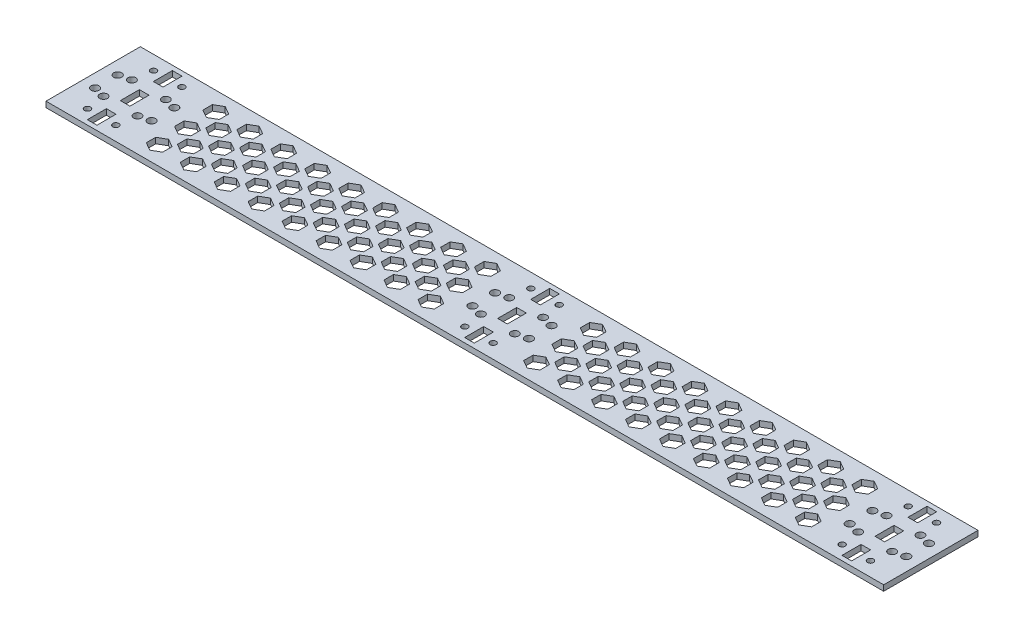
SolidWorks part; units mm, degrees
ref_plane "前视基准面" through (0, 0, 0) normal (0, 0, 1) x (1, 0, 0)
ref_plane "上视基准面" through (0, 0, 0) normal (0, 1, 0) x (1, 0, 0)
ref_plane "右视基准面" through (0, 0, 0) normal (1, 0, 0) x (0, 0, -1)
other "Configuration Table"
sketch "草图1" plane through (0, 0, 0) normal (0, 1, 0) x (1, 0, 0)
  line L0 (202.55, -5.05) -> (197.45, -5.05)
  line L1 (222, -25) -> (-222, -25)
  line L2 (222, -25) -> (222, 25)
  line L3 (222, 25) -> (-222, 25)
  line L4 (-222, -25) -> (-222, 25)
  line L5 (222, -25) -> (-222, 25) construction
  line L6 (222, 25) -> (-222, -25) construction
  line L7 (19, -10) -> (-19, -10) construction
  line L8 (19, -10) -> (19, 10) construction
  line L9 (19, 10) -> (-19, 10) construction
  line L10 (-19, -10) -> (-19, 10) construction
  line L11 (19, -10) -> (-19, 10) construction
  line L12 (19, 10) -> (-19, -10) construction
  line L13 (2.55, -5.05) -> (-2.55, -5.05)
  line L14 (2.55, -5.05) -> (2.55, 5.05)
  line L15 (2.55, 5.05) -> (-2.55, 5.05)
  line L16 (-2.55, -5.05) -> (-2.55, 5.05)
  line L17 (2.55, -5.05) -> (-2.55, 5.05) construction
  line L18 (2.55, 5.05) -> (-2.55, -5.05) construction
  line L19 (2.55, 12.45) -> (-2.55, 12.45)
  line L20 (2.55, 12.45) -> (2.55, 22.55)
  line L21 (2.55, 22.55) -> (-2.55, 22.55)
  line L22 (-2.55, 12.45) -> (-2.55, 22.55)
  line L23 (2.55, 12.45) -> (-2.55, 22.55) construction
  line L24 (2.55, 22.55) -> (-2.55, 12.45) construction
  line L25 (2.55, -22.55) -> (-2.55, -22.55)
  line L26 (2.55, -22.55) -> (2.55, -12.45)
  line L27 (2.55, -12.45) -> (-2.55, -12.45)
  line L28 (-2.55, -22.55) -> (-2.55, -12.45)
  line L29 (2.55, -22.55) -> (-2.55, -12.45) construction
  line L30 (2.55, -12.45) -> (-2.55, -22.55) construction
  line L31 (202.55, -5.05) -> (202.55, 5.05)
  line L32 (202.55, 5.05) -> (197.45, 5.05)
  line L33 (197.45, -5.05) -> (197.45, 5.05)
  line L34 (202.55, 12.45) -> (197.45, 12.45)
  line L35 (202.55, 12.45) -> (202.55, 22.55)
  line L36 (202.55, 22.55) -> (197.45, 22.55)
  line L37 (197.45, 12.45) -> (197.45, 22.55)
  line L38 (202.55, -22.55) -> (197.45, -22.55)
  line L39 (202.55, -22.55) -> (202.55, -12.45)
  line L40 (202.55, -12.45) -> (197.45, -12.45)
  line L41 (197.45, -22.55) -> (197.45, -12.45)
  line L42 (219, -10) -> (181, -10) construction
  line L43 (219, -10) -> (219, 10) construction
  line L44 (219, 10) -> (181, 10) construction
  line L45 (181, -10) -> (181, 10) construction
  line L46 (219, -10) -> (181, 10) construction
  line L47 (219, 10) -> (181, -10) construction
  line L48 (202.55, -5.05) -> (197.45, 5.05) construction
  line L49 (202.55, 5.05) -> (197.45, -5.05) construction
  line L50 (202.55, 12.45) -> (197.45, 22.55) construction
  line L51 (202.55, 22.55) -> (197.45, 12.45) construction
  line L52 (202.55, -22.55) -> (197.45, -12.45) construction
  line L53 (202.55, -12.45) -> (197.45, -22.55) construction
  line L54 (-197.45, -5.05) -> (-202.55, -5.05)
  line L55 (-197.45, -5.05) -> (-197.45, 5.05)
  line L56 (-197.45, 5.05) -> (-202.55, 5.05)
  line L57 (-202.55, -5.05) -> (-202.55, 5.05)
  line L58 (-197.45, 12.45) -> (-202.55, 12.45)
  line L59 (-197.45, 12.45) -> (-197.45, 22.55)
  line L60 (-197.45, 22.55) -> (-202.55, 22.55)
  line L61 (-202.55, 12.45) -> (-202.55, 22.55)
  line L62 (-197.45, -22.55) -> (-202.55, -22.55)
  line L63 (-197.45, -22.55) -> (-197.45, -12.45)
  line L64 (-197.45, -12.45) -> (-202.55, -12.45)
  line L65 (-202.55, -22.55) -> (-202.55, -12.45)
  line L66 (-181, -10) -> (-219, -10) construction
  line L67 (-181, -10) -> (-181, 10) construction
  line L68 (-181, 10) -> (-219, 10) construction
  line L69 (-219, -10) -> (-219, 10) construction
  line L70 (-181, -10) -> (-219, 10) construction
  line L71 (-181, 10) -> (-219, -10) construction
  line L72 (-197.45, -5.05) -> (-202.55, 5.05) construction
  line L73 (-197.45, 5.05) -> (-202.55, -5.05) construction
  line L74 (-197.45, 12.45) -> (-202.55, 22.55) construction
  line L75 (-197.45, 22.55) -> (-202.55, 12.45) construction
  line L76 (-197.45, -22.55) -> (-202.55, -12.45) construction
  line L77 (-197.45, -12.45) -> (-202.55, -22.55) construction
  line L78 (-55, 12.5) -> (-59.3301, 10)
  line L79 (-28, 5) -> (-32.3301, 2.5)
  line L80 (-32.3301, 2.5) -> (-32.3301, -2.5)
  line L81 (-32.3301, -2.5) -> (-28, -5)
  line L82 (-28, -5) -> (-23.6699, -2.5)
  line L83 (-23.6699, -2.5) -> (-23.6699, 2.5)
  line L84 (-23.6699, 2.5) -> (-28, 5)
  line L85 (-28, 20) -> (-32.3301, 17.5)
  line L86 (-32.3301, 17.5) -> (-32.3301, 12.5)
  line L87 (-32.3301, 12.5) -> (-28, 10)
  line L88 (-28, 10) -> (-23.6699, 12.5)
  line L89 (-23.6699, 12.5) -> (-23.6699, 17.5)
  line L90 (-23.6699, 17.5) -> (-28, 20)
  line L91 (-28, -20) -> (-23.6699, -17.5)
  line L92 (-23.6699, -17.5) -> (-23.6699, -12.5)
  line L93 (-23.6699, -12.5) -> (-28, -10)
  line L94 (-28, -10) -> (-32.3301, -12.5)
  line L95 (-32.3301, -12.5) -> (-32.3301, -17.5)
  line L96 (-32.3301, -17.5) -> (-28, -20)
  line L97 (-37, 12.5) -> (-41.3301, 10)
  line L98 (-41.3301, 10) -> (-41.3301, 5)
  line L99 (-41.3301, 5) -> (-37, 2.5)
  line L100 (-37, 2.5) -> (-32.6699, 5)
  line L101 (-32.6699, 5) -> (-32.6699, 10)
  line L102 (-32.6699, 10) -> (-37, 12.5)
  line L103 (-37, -12.5) -> (-32.6699, -10)
  line L104 (-32.6699, -10) -> (-32.6699, -5)
  line L105 (-32.6699, -5) -> (-37, -2.5)
  line L106 (-37, -2.5) -> (-41.3301, -5)
  line L107 (-41.3301, -5) -> (-41.3301, -10)
  line L108 (-41.3301, -10) -> (-37, -12.5)
  line L109 (-59.3301, 10) -> (-59.3301, 5)
  line L110 (-59.3301, 5) -> (-55, 2.5)
  line L111 (-55, 2.5) -> (-50.6699, 5)
  line L112 (-50.6699, 5) -> (-50.6699, 10)
  line L113 (-50.6699, 10) -> (-55, 12.5)
  line L114 (-46, 20) -> (-50.3301, 17.5)
  line L115 (-50.3301, 17.5) -> (-50.3301, 12.5)
  line L116 (-50.3301, 12.5) -> (-46, 10)
  line L117 (-46, 10) -> (-41.6699, 12.5)
  line L118 (-41.6699, 12.5) -> (-41.6699, 17.5)
  line L119 (-41.6699, 17.5) -> (-46, 20)
  line L120 (-46, -20) -> (-41.6699, -17.5)
  line L121 (-41.6699, -17.5) -> (-41.6699, -12.5)
  line L122 (-41.6699, -12.5) -> (-46, -10)
  line L123 (-46, -10) -> (-50.3301, -12.5)
  line L124 (-50.3301, -12.5) -> (-50.3301, -17.5)
  line L125 (-50.3301, -17.5) -> (-46, -20)
  line L126 (-55, -12.5) -> (-50.6699, -10)
  line L127 (-50.6699, -10) -> (-50.6699, -5)
  line L128 (-50.6699, -5) -> (-55, -2.5)
  line L129 (-55, -2.5) -> (-59.3301, -5)
  line L130 (-59.3301, -5) -> (-59.3301, -10)
  line L131 (-59.3301, -10) -> (-55, -12.5)
  line L132 (-46, 5) -> (-50.3301, 2.5)
  line L133 (-50.3301, 2.5) -> (-50.3301, -2.5)
  line L134 (-50.3301, -2.5) -> (-46, -5)
  line L135 (-46, -5) -> (-41.6699, -2.5)
  line L136 (-41.6699, -2.5) -> (-41.6699, 2.5)
  line L137 (-41.6699, 2.5) -> (-46, 5)
  line L138 (-73, 12.5) -> (-77.3301, 10)
  line L139 (-77.3301, 10) -> (-77.3301, 5)
  line L140 (-77.3301, 5) -> (-73, 2.5)
  line L141 (-73, 2.5) -> (-68.6699, 5)
  line L142 (-68.6699, 5) -> (-68.6699, 10)
  line L143 (-68.6699, 10) -> (-73, 12.5)
  line L144 (-64, 20) -> (-68.3301, 17.5)
  line L145 (-68.3301, 17.5) -> (-68.3301, 12.5)
  line L146 (-68.3301, 12.5) -> (-64, 10)
  line L147 (-64, 10) -> (-59.6699, 12.5)
  line L148 (-59.6699, 12.5) -> (-59.6699, 17.5)
  line L149 (-59.6699, 17.5) -> (-64, 20)
  line L150 (-64, -20) -> (-59.6699, -17.5)
  line L151 (-59.6699, -17.5) -> (-59.6699, -12.5)
  line L152 (-59.6699, -12.5) -> (-64, -10)
  line L153 (-64, -10) -> (-68.3301, -12.5)
  line L154 (-68.3301, -12.5) -> (-68.3301, -17.5)
  line L155 (-68.3301, -17.5) -> (-64, -20)
  line L156 (-73, -12.5) -> (-68.6699, -10)
  line L157 (-68.6699, -10) -> (-68.6699, -5)
  line L158 (-68.6699, -5) -> (-73, -2.5)
  line L159 (-73, -2.5) -> (-77.3301, -5)
  line L160 (-77.3301, -5) -> (-77.3301, -10)
  line L161 (-77.3301, -10) -> (-73, -12.5)
  line L162 (-64, 5) -> (-68.3301, 2.5)
  line L163 (-68.3301, 2.5) -> (-68.3301, -2.5)
  line L164 (-68.3301, -2.5) -> (-64, -5)
  line L165 (-64, -5) -> (-59.6699, -2.5)
  line L166 (-59.6699, -2.5) -> (-59.6699, 2.5)
  line L167 (-59.6699, 2.5) -> (-64, 5)
  line L168 (-91, 12.5) -> (-95.3301, 10)
  line L169 (-95.3301, 10) -> (-95.3301, 5)
  line L170 (-95.3301, 5) -> (-91, 2.5)
  line L171 (-91, 2.5) -> (-86.6699, 5)
  line L172 (-86.6699, 5) -> (-86.6699, 10)
  line L173 (-86.6699, 10) -> (-91, 12.5)
  line L174 (-82, 20) -> (-86.3301, 17.5)
  line L175 (-86.3301, 17.5) -> (-86.3301, 12.5)
  line L176 (-86.3301, 12.5) -> (-82, 10)
  line L177 (-82, 10) -> (-77.6699, 12.5)
  line L178 (-77.6699, 12.5) -> (-77.6699, 17.5)
  line L179 (-77.6699, 17.5) -> (-82, 20)
  line L180 (-82, -20) -> (-77.6699, -17.5)
  line L181 (-77.6699, -17.5) -> (-77.6699, -12.5)
  line L182 (-77.6699, -12.5) -> (-82, -10)
  line L183 (-82, -10) -> (-86.3301, -12.5)
  line L184 (-86.3301, -12.5) -> (-86.3301, -17.5)
  line L185 (-86.3301, -17.5) -> (-82, -20)
  line L186 (-91, -12.5) -> (-86.6699, -10)
  line L187 (-86.6699, -10) -> (-86.6699, -5)
  line L188 (-86.6699, -5) -> (-91, -2.5)
  line L189 (-91, -2.5) -> (-95.3301, -5)
  line L190 (-95.3301, -5) -> (-95.3301, -10)
  line L191 (-95.3301, -10) -> (-91, -12.5)
  line L192 (-82, 5) -> (-86.3301, 2.5)
  line L193 (-86.3301, 2.5) -> (-86.3301, -2.5)
  line L194 (-86.3301, -2.5) -> (-82, -5)
  line L195 (-82, -5) -> (-77.6699, -2.5)
  line L196 (-77.6699, -2.5) -> (-77.6699, 2.5)
  line L197 (-77.6699, 2.5) -> (-82, 5)
  line L198 (-109, 12.5) -> (-113.3301, 10)
  line L199 (-113.3301, 10) -> (-113.3301, 5)
  line L200 (-113.3301, 5) -> (-109, 2.5)
  line L201 (-109, 2.5) -> (-104.6699, 5)
  line L202 (-104.6699, 5) -> (-104.6699, 10)
  line L203 (-104.6699, 10) -> (-109, 12.5)
  line L204 (-100, 20) -> (-104.3301, 17.5)
  line L205 (-104.3301, 17.5) -> (-104.3301, 12.5)
  line L206 (-104.3301, 12.5) -> (-100, 10)
  line L207 (-100, 10) -> (-95.6699, 12.5)
  line L208 (-95.6699, 12.5) -> (-95.6699, 17.5)
  line L209 (-95.6699, 17.5) -> (-100, 20)
  line L210 (-100, -20) -> (-95.6699, -17.5)
  line L211 (-95.6699, -17.5) -> (-95.6699, -12.5)
  line L212 (-95.6699, -12.5) -> (-100, -10)
  line L213 (-100, -10) -> (-104.3301, -12.5)
  line L214 (-104.3301, -12.5) -> (-104.3301, -17.5)
  line L215 (-104.3301, -17.5) -> (-100, -20)
  line L216 (-109, -12.5) -> (-104.6699, -10)
  line L217 (-104.6699, -10) -> (-104.6699, -5)
  line L218 (-104.6699, -5) -> (-109, -2.5)
  line L219 (-109, -2.5) -> (-113.3301, -5)
  line L220 (-113.3301, -5) -> (-113.3301, -10)
  line L221 (-113.3301, -10) -> (-109, -12.5)
  line L222 (-100, 5) -> (-104.3301, 2.5)
  line L223 (-104.3301, 2.5) -> (-104.3301, -2.5)
  line L224 (-104.3301, -2.5) -> (-100, -5)
  line L225 (-100, -5) -> (-95.6699, -2.5)
  line L226 (-95.6699, -2.5) -> (-95.6699, 2.5)
  line L227 (-95.6699, 2.5) -> (-100, 5)
  line L228 (-127, 12.5) -> (-131.3301, 10)
  line L229 (-131.3301, 10) -> (-131.3301, 5)
  line L230 (-131.3301, 5) -> (-127, 2.5)
  line L231 (-127, 2.5) -> (-122.6699, 5)
  line L232 (-122.6699, 5) -> (-122.6699, 10)
  line L233 (-122.6699, 10) -> (-127, 12.5)
  line L234 (-118, 20) -> (-122.3301, 17.5)
  line L235 (-122.3301, 17.5) -> (-122.3301, 12.5)
  line L236 (-122.3301, 12.5) -> (-118, 10)
  line L237 (-118, 10) -> (-113.6699, 12.5)
  line L238 (-113.6699, 12.5) -> (-113.6699, 17.5)
  line L239 (-113.6699, 17.5) -> (-118, 20)
  line L240 (-118, -20) -> (-113.6699, -17.5)
  line L241 (-113.6699, -17.5) -> (-113.6699, -12.5)
  line L242 (-113.6699, -12.5) -> (-118, -10)
  line L243 (-118, -10) -> (-122.3301, -12.5)
  line L244 (-122.3301, -12.5) -> (-122.3301, -17.5)
  line L245 (-122.3301, -17.5) -> (-118, -20)
  line L246 (-127, -12.5) -> (-122.6699, -10)
  line L247 (-122.6699, -10) -> (-122.6699, -5)
  line L248 (-122.6699, -5) -> (-127, -2.5)
  line L249 (-127, -2.5) -> (-131.3301, -5)
  line L250 (-131.3301, -5) -> (-131.3301, -10)
  line L251 (-131.3301, -10) -> (-127, -12.5)
  line L252 (-118, 5) -> (-122.3301, 2.5)
  line L253 (-122.3301, 2.5) -> (-122.3301, -2.5)
  line L254 (-122.3301, -2.5) -> (-118, -5)
  line L255 (-118, -5) -> (-113.6699, -2.5)
  line L256 (-113.6699, -2.5) -> (-113.6699, 2.5)
  line L257 (-113.6699, 2.5) -> (-118, 5)
  line L258 (-145, 12.5) -> (-149.3301, 10)
  line L259 (-149.3301, 10) -> (-149.3301, 5)
  line L260 (-149.3301, 5) -> (-145, 2.5)
  line L261 (-145, 2.5) -> (-140.6699, 5)
  line L262 (-140.6699, 5) -> (-140.6699, 10)
  line L263 (-140.6699, 10) -> (-145, 12.5)
  line L264 (-136, 20) -> (-140.3301, 17.5)
  line L265 (-140.3301, 17.5) -> (-140.3301, 12.5)
  line L266 (-140.3301, 12.5) -> (-136, 10)
  line L267 (-136, 10) -> (-131.6699, 12.5)
  line L268 (-131.6699, 12.5) -> (-131.6699, 17.5)
  line L269 (-131.6699, 17.5) -> (-136, 20)
  line L270 (-136, -20) -> (-131.6699, -17.5)
  line L271 (-131.6699, -17.5) -> (-131.6699, -12.5)
  line L272 (-131.6699, -12.5) -> (-136, -10)
  line L273 (-136, -10) -> (-140.3301, -12.5)
  line L274 (-140.3301, -12.5) -> (-140.3301, -17.5)
  line L275 (-140.3301, -17.5) -> (-136, -20)
  line L276 (-145, -12.5) -> (-140.6699, -10)
  line L277 (-140.6699, -10) -> (-140.6699, -5)
  line L278 (-140.6699, -5) -> (-145, -2.5)
  line L279 (-145, -2.5) -> (-149.3301, -5)
  line L280 (-149.3301, -5) -> (-149.3301, -10)
  line L281 (-149.3301, -10) -> (-145, -12.5)
  line L282 (-136, 5) -> (-140.3301, 2.5)
  line L283 (-140.3301, 2.5) -> (-140.3301, -2.5)
  line L284 (-140.3301, -2.5) -> (-136, -5)
  line L285 (-136, -5) -> (-131.6699, -2.5)
  line L286 (-131.6699, -2.5) -> (-131.6699, 2.5)
  line L287 (-131.6699, 2.5) -> (-136, 5)
  line L288 (-163, 12.5) -> (-167.3301, 10)
  line L289 (-167.3301, 10) -> (-167.3301, 5)
  line L290 (-167.3301, 5) -> (-163, 2.5)
  line L291 (-163, 2.5) -> (-158.6699, 5)
  line L292 (-158.6699, 5) -> (-158.6699, 10)
  line L293 (-158.6699, 10) -> (-163, 12.5)
  line L294 (-154, 20) -> (-158.3301, 17.5)
  line L295 (-158.3301, 17.5) -> (-158.3301, 12.5)
  line L296 (-158.3301, 12.5) -> (-154, 10)
  line L297 (-154, 10) -> (-149.6699, 12.5)
  line L298 (-149.6699, 12.5) -> (-149.6699, 17.5)
  line L299 (-149.6699, 17.5) -> (-154, 20)
  line L300 (-154, -20) -> (-149.6699, -17.5)
  line L301 (-149.6699, -17.5) -> (-149.6699, -12.5)
  line L302 (-149.6699, -12.5) -> (-154, -10)
  line L303 (-154, -10) -> (-158.3301, -12.5)
  line L304 (-158.3301, -12.5) -> (-158.3301, -17.5)
  line L305 (-158.3301, -17.5) -> (-154, -20)
  line L306 (-163, -12.5) -> (-158.6699, -10)
  line L307 (-158.6699, -10) -> (-158.6699, -5)
  line L308 (-158.6699, -5) -> (-163, -2.5)
  line L309 (-163, -2.5) -> (-167.3301, -5)
  line L310 (-167.3301, -5) -> (-167.3301, -10)
  line L311 (-167.3301, -10) -> (-163, -12.5)
  line L312 (-154, 5) -> (-158.3301, 2.5)
  line L313 (-158.3301, 2.5) -> (-158.3301, -2.5)
  line L314 (-158.3301, -2.5) -> (-154, -5)
  line L315 (-154, -5) -> (-149.6699, -2.5)
  line L316 (-149.6699, -2.5) -> (-149.6699, 2.5)
  line L317 (-149.6699, 2.5) -> (-154, 5)
  line L318 (-172, 20) -> (-176.3301, 17.5)
  line L319 (-176.3301, 17.5) -> (-176.3301, 12.5)
  line L320 (-176.3301, 12.5) -> (-172, 10)
  line L321 (-172, 10) -> (-167.6699, 12.5)
  line L322 (-167.6699, 12.5) -> (-167.6699, 17.5)
  line L323 (-167.6699, 17.5) -> (-172, 20)
  line L324 (-172, 5) -> (-176.3301, 2.5)
  line L325 (-176.3301, 2.5) -> (-176.3301, -2.5)
  line L326 (-176.3301, -2.5) -> (-172, -5)
  line L327 (-172, -5) -> (-167.6699, -2.5)
  line L328 (-167.6699, -2.5) -> (-167.6699, 2.5)
  line L329 (-167.6699, 2.5) -> (-172, 5)
  line L330 (-172, -20) -> (-167.6699, -17.5)
  line L331 (-167.6699, -17.5) -> (-167.6699, -12.5)
  line L332 (-167.6699, -12.5) -> (-172, -10)
  line L333 (-172, -10) -> (-176.3301, -12.5)
  line L334 (-176.3301, -12.5) -> (-176.3301, -17.5)
  line L335 (-176.3301, -17.5) -> (-172, -20)
  line L336 (0, 45.3453) -> (0, -42.6317) construction
  line L337 (23.6699, 17.5) -> (28, 20)
  line L338 (23.6699, 12.5) -> (23.6699, 17.5)
  line L339 (28, 10) -> (23.6699, 12.5)
  line L340 (32.3301, 12.5) -> (28, 10)
  line L341 (32.3301, 17.5) -> (32.3301, 12.5)
  line L342 (28, 20) -> (32.3301, 17.5)
  line L343 (23.6699, 2.5) -> (28, 5)
  line L344 (23.6699, -2.5) -> (23.6699, 2.5)
  line L345 (28, -5) -> (23.6699, -2.5)
  line L346 (32.3301, -2.5) -> (28, -5)
  line L347 (32.3301, 2.5) -> (32.3301, -2.5)
  line L348 (28, 5) -> (32.3301, 2.5)
  line L349 (32.3301, -17.5) -> (28, -20)
  line L350 (32.3301, -12.5) -> (32.3301, -17.5)
  line L351 (28, -10) -> (32.3301, -12.5)
  line L352 (23.6699, -12.5) -> (28, -10)
  line L353 (23.6699, -17.5) -> (23.6699, -12.5)
  line L354 (28, -20) -> (23.6699, -17.5)
  line L355 (32.6699, 10) -> (37, 12.5)
  line L356 (32.6699, 5) -> (32.6699, 10)
  line L357 (37, 2.5) -> (32.6699, 5)
  line L358 (41.3301, 5) -> (37, 2.5)
  line L359 (41.3301, 10) -> (41.3301, 5)
  line L360 (37, 12.5) -> (41.3301, 10)
  line L361 (41.3301, -10) -> (37, -12.5)
  line L362 (41.3301, -5) -> (41.3301, -10)
  line L363 (37, -2.5) -> (41.3301, -5)
  line L364 (32.6699, -5) -> (37, -2.5)
  line L365 (32.6699, -10) -> (32.6699, -5)
  line L366 (37, -12.5) -> (32.6699, -10)
  line L367 (50.3301, -17.5) -> (46, -20)
  line L368 (50.3301, -12.5) -> (50.3301, -17.5)
  line L369 (46, -10) -> (50.3301, -12.5)
  line L370 (41.6699, -12.5) -> (46, -10)
  line L371 (41.6699, -17.5) -> (41.6699, -12.5)
  line L372 (46, -20) -> (41.6699, -17.5)
  line L373 (41.6699, 2.5) -> (46, 5)
  line L374 (41.6699, -2.5) -> (41.6699, 2.5)
  line L375 (46, -5) -> (41.6699, -2.5)
  line L376 (50.3301, -2.5) -> (46, -5)
  line L377 (50.3301, 2.5) -> (50.3301, -2.5)
  line L378 (46, 5) -> (50.3301, 2.5)
  line L379 (41.6699, 17.5) -> (46, 20)
  line L380 (41.6699, 12.5) -> (41.6699, 17.5)
  line L381 (46, 10) -> (41.6699, 12.5)
  line L382 (50.3301, 12.5) -> (46, 10)
  line L383 (50.3301, 17.5) -> (50.3301, 12.5)
  line L384 (46, 20) -> (50.3301, 17.5)
  line L385 (50.6699, 10) -> (55, 12.5)
  line L386 (50.6699, 5) -> (50.6699, 10)
  line L387 (55, 2.5) -> (50.6699, 5)
  line L388 (59.3301, 5) -> (55, 2.5)
  line L389 (59.3301, 10) -> (59.3301, 5)
  line L390 (55, 12.5) -> (59.3301, 10)
  line L391 (59.3301, -10) -> (55, -12.5)
  line L392 (59.3301, -5) -> (59.3301, -10)
  line L393 (55, -2.5) -> (59.3301, -5)
  line L394 (50.6699, -5) -> (55, -2.5)
  line L395 (50.6699, -10) -> (50.6699, -5)
  line L396 (55, -12.5) -> (50.6699, -10)
  line L397 (68.3301, -17.5) -> (64, -20)
  line L398 (68.3301, -12.5) -> (68.3301, -17.5)
  line L399 (64, -10) -> (68.3301, -12.5)
  line L400 (59.6699, -12.5) -> (64, -10)
  line L401 (59.6699, -17.5) -> (59.6699, -12.5)
  line L402 (64, -20) -> (59.6699, -17.5)
  line L403 (59.6699, 2.5) -> (64, 5)
  line L404 (59.6699, -2.5) -> (59.6699, 2.5)
  line L405 (64, -5) -> (59.6699, -2.5)
  line L406 (68.3301, -2.5) -> (64, -5)
  line L407 (68.3301, 2.5) -> (68.3301, -2.5)
  line L408 (64, 5) -> (68.3301, 2.5)
  line L409 (59.6699, 17.5) -> (64, 20)
  line L410 (59.6699, 12.5) -> (59.6699, 17.5)
  line L411 (64, 10) -> (59.6699, 12.5)
  line L412 (68.3301, 12.5) -> (64, 10)
  line L413 (68.3301, 17.5) -> (68.3301, 12.5)
  line L414 (64, 20) -> (68.3301, 17.5)
  line L415 (68.6699, 10) -> (73, 12.5)
  line L416 (68.6699, 5) -> (68.6699, 10)
  line L417 (73, 2.5) -> (68.6699, 5)
  line L418 (77.3301, 5) -> (73, 2.5)
  line L419 (77.3301, 10) -> (77.3301, 5)
  line L420 (73, 12.5) -> (77.3301, 10)
  line L421 (77.3301, -10) -> (73, -12.5)
  line L422 (77.3301, -5) -> (77.3301, -10)
  line L423 (73, -2.5) -> (77.3301, -5)
  line L424 (68.6699, -5) -> (73, -2.5)
  line L425 (68.6699, -10) -> (68.6699, -5)
  line L426 (73, -12.5) -> (68.6699, -10)
  line L427 (86.3301, -17.5) -> (82, -20)
  line L428 (86.3301, -12.5) -> (86.3301, -17.5)
  line L429 (82, -10) -> (86.3301, -12.5)
  line L430 (77.6699, -12.5) -> (82, -10)
  line L431 (77.6699, -17.5) -> (77.6699, -12.5)
  line L432 (82, -20) -> (77.6699, -17.5)
  line L433 (77.6699, 17.5) -> (82, 20)
  line L434 (77.6699, 12.5) -> (77.6699, 17.5)
  line L435 (82, 10) -> (77.6699, 12.5)
  line L436 (86.3301, 12.5) -> (82, 10)
  line L437 (86.3301, 17.5) -> (86.3301, 12.5)
  line L438 (82, 20) -> (86.3301, 17.5)
  line L439 (86.6699, 10) -> (91, 12.5)
  line L440 (86.6699, 5) -> (86.6699, 10)
  line L441 (91, 2.5) -> (86.6699, 5)
  line L442 (95.3301, 5) -> (91, 2.5)
  line L443 (95.3301, 10) -> (95.3301, 5)
  line L444 (91, 12.5) -> (95.3301, 10)
  line L445 (77.6699, 2.5) -> (82, 5)
  line L446 (77.6699, -2.5) -> (77.6699, 2.5)
  line L447 (82, -5) -> (77.6699, -2.5)
  line L448 (86.3301, -2.5) -> (82, -5)
  line L449 (86.3301, 2.5) -> (86.3301, -2.5)
  line L450 (82, 5) -> (86.3301, 2.5)
  line L451 (95.3301, -10) -> (91, -12.5)
  line L452 (95.3301, -5) -> (95.3301, -10)
  line L453 (91, -2.5) -> (95.3301, -5)
  line L454 (86.6699, -5) -> (91, -2.5)
  line L455 (86.6699, -10) -> (86.6699, -5)
  line L456 (91, -12.5) -> (86.6699, -10)
  line L457 (104.3301, -17.5) -> (100, -20)
  line L458 (104.3301, -12.5) -> (104.3301, -17.5)
  line L459 (100, -10) -> (104.3301, -12.5)
  line L460 (95.6699, -12.5) -> (100, -10)
  line L461 (95.6699, -17.5) -> (95.6699, -12.5)
  line L462 (100, -20) -> (95.6699, -17.5)
  line L463 (95.6699, 2.5) -> (100, 5)
  line L464 (95.6699, -2.5) -> (95.6699, 2.5)
  line L465 (100, -5) -> (95.6699, -2.5)
  line L466 (104.3301, -2.5) -> (100, -5)
  line L467 (104.3301, 2.5) -> (104.3301, -2.5)
  line L468 (100, 5) -> (104.3301, 2.5)
  line L469 (95.6699, 17.5) -> (100, 20)
  line L470 (95.6699, 12.5) -> (95.6699, 17.5)
  line L471 (100, 10) -> (95.6699, 12.5)
  line L472 (104.3301, 12.5) -> (100, 10)
  line L473 (104.3301, 17.5) -> (104.3301, 12.5)
  line L474 (100, 20) -> (104.3301, 17.5)
  line L475 (113.3301, -10) -> (109, -12.5)
  line L476 (113.3301, -5) -> (113.3301, -10)
  line L477 (109, -2.5) -> (113.3301, -5)
  line L478 (104.6699, -5) -> (109, -2.5)
  line L479 (104.6699, -10) -> (104.6699, -5)
  line L480 (109, -12.5) -> (104.6699, -10)
  line L481 (104.6699, 10) -> (109, 12.5)
  line L482 (104.6699, 5) -> (104.6699, 10)
  line L483 (109, 2.5) -> (104.6699, 5)
  line L484 (113.3301, 5) -> (109, 2.5)
  line L485 (113.3301, 10) -> (113.3301, 5)
  line L486 (109, 12.5) -> (113.3301, 10)
  line L487 (122.3301, -17.5) -> (118, -20)
  line L488 (122.3301, -12.5) -> (122.3301, -17.5)
  line L489 (118, -10) -> (122.3301, -12.5)
  line L490 (113.6699, -12.5) -> (118, -10)
  line L491 (113.6699, -17.5) -> (113.6699, -12.5)
  line L492 (118, -20) -> (113.6699, -17.5)
  line L493 (113.6699, 2.5) -> (118, 5)
  line L494 (113.6699, -2.5) -> (113.6699, 2.5)
  line L495 (118, -5) -> (113.6699, -2.5)
  line L496 (122.3301, -2.5) -> (118, -5)
  line L497 (122.3301, 2.5) -> (122.3301, -2.5)
  line L498 (118, 5) -> (122.3301, 2.5)
  line L499 (113.6699, 17.5) -> (118, 20)
  line L500 (113.6699, 12.5) -> (113.6699, 17.5)
  line L501 (118, 10) -> (113.6699, 12.5)
  line L502 (122.3301, 12.5) -> (118, 10)
  line L503 (122.3301, 17.5) -> (122.3301, 12.5)
  line L504 (118, 20) -> (122.3301, 17.5)
  line L505 (122.6699, 10) -> (127, 12.5)
  line L506 (122.6699, 5) -> (122.6699, 10)
  line L507 (127, 2.5) -> (122.6699, 5)
  line L508 (131.3301, 5) -> (127, 2.5)
  line L509 (131.3301, 10) -> (131.3301, 5)
  line L510 (127, 12.5) -> (131.3301, 10)
  line L511 (131.3301, -10) -> (127, -12.5)
  line L512 (131.3301, -5) -> (131.3301, -10)
  line L513 (127, -2.5) -> (131.3301, -5)
  line L514 (122.6699, -5) -> (127, -2.5)
  line L515 (122.6699, -10) -> (122.6699, -5)
  line L516 (127, -12.5) -> (122.6699, -10)
  line L517 (140.3301, -17.5) -> (136, -20)
  line L518 (140.3301, -12.5) -> (140.3301, -17.5)
  line L519 (136, -10) -> (140.3301, -12.5)
  line L520 (131.6699, -12.5) -> (136, -10)
  line L521 (131.6699, -17.5) -> (131.6699, -12.5)
  line L522 (136, -20) -> (131.6699, -17.5)
  line L523 (131.6699, 2.5) -> (136, 5)
  line L524 (131.6699, -2.5) -> (131.6699, 2.5)
  line L525 (136, -5) -> (131.6699, -2.5)
  line L526 (140.3301, -2.5) -> (136, -5)
  line L527 (140.3301, 2.5) -> (140.3301, -2.5)
  line L528 (136, 5) -> (140.3301, 2.5)
  line L529 (131.6699, 17.5) -> (136, 20)
  line L530 (131.6699, 12.5) -> (131.6699, 17.5)
  line L531 (136, 10) -> (131.6699, 12.5)
  line L532 (140.3301, 12.5) -> (136, 10)
  line L533 (140.3301, 17.5) -> (140.3301, 12.5)
  line L534 (136, 20) -> (140.3301, 17.5)
  line L535 (140.6699, 10) -> (145, 12.5)
  line L536 (140.6699, 5) -> (140.6699, 10)
  line L537 (145, 2.5) -> (140.6699, 5)
  line L538 (149.3301, 5) -> (145, 2.5)
  line L539 (149.3301, 10) -> (149.3301, 5)
  line L540 (145, 12.5) -> (149.3301, 10)
  line L541 (149.3301, -10) -> (145, -12.5)
  line L542 (149.3301, -5) -> (149.3301, -10)
  line L543 (145, -2.5) -> (149.3301, -5)
  line L544 (140.6699, -5) -> (145, -2.5)
  line L545 (140.6699, -10) -> (140.6699, -5)
  line L546 (145, -12.5) -> (140.6699, -10)
  line L547 (158.3301, -17.5) -> (154, -20)
  line L548 (158.3301, -12.5) -> (158.3301, -17.5)
  line L549 (154, -10) -> (158.3301, -12.5)
  line L550 (149.6699, -12.5) -> (154, -10)
  line L551 (149.6699, -17.5) -> (149.6699, -12.5)
  line L552 (154, -20) -> (149.6699, -17.5)
  line L553 (149.6699, 2.5) -> (154, 5)
  line L554 (149.6699, -2.5) -> (149.6699, 2.5)
  line L555 (154, -5) -> (149.6699, -2.5)
  line L556 (158.3301, -2.5) -> (154, -5)
  line L557 (158.3301, 2.5) -> (158.3301, -2.5)
  line L558 (154, 5) -> (158.3301, 2.5)
  line L559 (149.6699, 17.5) -> (154, 20)
  line L560 (149.6699, 12.5) -> (149.6699, 17.5)
  line L561 (154, 10) -> (149.6699, 12.5)
  line L562 (158.3301, 12.5) -> (154, 10)
  line L563 (158.3301, 17.5) -> (158.3301, 12.5)
  line L564 (154, 20) -> (158.3301, 17.5)
  line L565 (158.6699, 10) -> (163, 12.5)
  line L566 (158.6699, 5) -> (158.6699, 10)
  line L567 (163, 2.5) -> (158.6699, 5)
  line L568 (167.3301, 5) -> (163, 2.5)
  line L569 (167.3301, 10) -> (167.3301, 5)
  line L570 (163, 12.5) -> (167.3301, 10)
  line L571 (167.3301, -10) -> (163, -12.5)
  line L572 (167.3301, -5) -> (167.3301, -10)
  line L573 (163, -2.5) -> (167.3301, -5)
  line L574 (158.6699, -5) -> (163, -2.5)
  line L575 (158.6699, -10) -> (158.6699, -5)
  line L576 (163, -12.5) -> (158.6699, -10)
  line L577 (176.3301, -17.5) -> (172, -20)
  line L578 (176.3301, -12.5) -> (176.3301, -17.5)
  line L579 (172, -10) -> (176.3301, -12.5)
  line L580 (167.6699, -12.5) -> (172, -10)
  line L581 (167.6699, -17.5) -> (167.6699, -12.5)
  line L582 (172, -20) -> (167.6699, -17.5)
  line L583 (167.6699, 2.5) -> (172, 5)
  line L584 (167.6699, -2.5) -> (167.6699, 2.5)
  line L585 (172, -5) -> (167.6699, -2.5)
  line L586 (176.3301, -2.5) -> (172, -5)
  line L587 (176.3301, 2.5) -> (176.3301, -2.5)
  line L588 (172, 5) -> (176.3301, 2.5)
  line L589 (167.6699, 17.5) -> (172, 20)
  line L590 (167.6699, 12.5) -> (167.6699, 17.5)
  line L591 (172, 10) -> (167.6699, 12.5)
  line L592 (176.3301, 12.5) -> (172, 10)
  line L593 (176.3301, 17.5) -> (176.3301, 12.5)
  line L594 (172, 20) -> (176.3301, 17.5)
  circle A0 centre (0, 0) radius 8.5 construction
  circle A1 centre (-15, 6) radius 2.1
  circle A2 centre (15, 6) radius 2.1
  circle A3 centre (15, -6) radius 2.1
  circle A4 centre (-15, -6) radius 2.1
  circle A5 centre (-9, 7.5) radius 2.05
  circle A6 centre (9, 7.5) radius 2.05
  circle A7 centre (9, -7.5) radius 2.05
  circle A8 centre (-9, -7.5) radius 2.05
  circle A9 centre (7.5, -17.5) radius 1.6
  circle A10 centre (-7.5, -17.5) radius 1.6
  circle A11 centre (7.5, 17.5) radius 1.6
  circle A12 centre (-7.5, 17.5) radius 1.6
  circle A13 centre (185, 6) radius 2.1
  circle A14 centre (215, 6) radius 2.1
  circle A15 centre (215, -6) radius 2.1
  circle A16 centre (185, -6) radius 2.1
  circle A17 centre (191, 7.5) radius 2.05
  circle A18 centre (209, 7.5) radius 2.05
  circle A19 centre (209, -7.5) radius 2.05
  circle A20 centre (191, -7.5) radius 2.05
  circle A21 centre (207.5, -17.5) radius 1.6
  circle A22 centre (192.5, -17.5) radius 1.6
  circle A23 centre (207.5, 17.5) radius 1.6
  circle A24 centre (192.5, 17.5) radius 1.6
  circle A25 centre (200, 0) radius 8.5 construction
  circle A26 centre (-215, 6) radius 2.1
  circle A27 centre (-185, 6) radius 2.1
  circle A28 centre (-185, -6) radius 2.1
  circle A29 centre (-215, -6) radius 2.1
  circle A30 centre (-209, 7.5) radius 2.05
  circle A31 centre (-191, 7.5) radius 2.05
  circle A32 centre (-191, -7.5) radius 2.05
  circle A33 centre (-209, -7.5) radius 2.05
  circle A34 centre (-192.5, -17.5) radius 1.6
  circle A35 centre (-207.5, -17.5) radius 1.6
  circle A36 centre (-192.5, 17.5) radius 1.6
  circle A37 centre (-207.5, 17.5) radius 1.6
  circle A38 centre (-200, 0) radius 8.5 construction
  circle A39 centre (-28, 0) radius 4.3301 construction
  circle A40 centre (-28, 15) radius 4.3301 construction
  circle A41 centre (-28, -15) radius 4.3301 construction
  circle A42 centre (-37, 7.5) radius 4.3301 construction
  circle A43 centre (-37, -7.5) radius 4.3301 construction
  point P0 (0, 0)
  point P6 (0, 0)
  point P31 (0, 17.5)
  point P38 (0, 22.55)
  point P39 (0, -17.5)
  point P52 (200, 0)
  point P53 (200, 0)
  point P79 (200, 17.5)
  point P86 (200, -17.5)
  point P99 (-200, 0)
  point P100 (-200, 0)
  point P125 (-200, 17.5)
  point P132 (-200, -17.5)
  dimension "D5" = 17
  dimension "D6" = 4.2
  dimension "D15" = 4.1
  dimension "D34" = 3.2
  dimension "D39" = 3.2
  dimension "D1" = 50
  dimension "D2" = 444
  dimension "D3" = 38
  dimension "D4" = 20
  dimension "D7" = 15
  dimension "D8" = 15
  dimension "D9" = 6
  dimension "D10" = 6
  dimension "D11" = 6
  dimension "D12" = 6
  dimension "D13" = 15
  dimension "D14" = 15
  dimension "D16" = 10
  dimension "D17" = 5
  dimension "D18" = 10
  dimension "D19" = 5
  dimension "D20" = 10
  dimension "D21" = 10
  dimension "D22" = 5
  dimension "D23" = 5
  dimension "D24" = 5.1
  dimension "D25" = 10.1
  dimension "D26" = 5.1
  dimension "D27" = 10.1
  dimension "D28" = 2.45
  dimension "D29" = 0
  dimension "D30" = 17.5
  dimension "D31" = 10.1
  dimension "D32" = 5.1
  dimension "D33" = 0
  dimension "D35" = 7.5
  dimension "D36" = 7.5
  dimension "D37" = 7.5
  dimension "D38" = 7.5
  dimension "D40" = 7.5
  dimension "D41" = 7.5
  dimension "D42" = 7.5
  dimension "D43" = 7.5
  dimension "D46" = 5
  dimension "D47" = 25
  dimension "D48" = 15
  dimension "D49" = 15
  dimension "D50" = 9
  dimension "D51" = 17.5
  dimension "D52" = 17.5
  dimension "D53" = 9
  dimension "D54" = 9
  dimension "D44" = 2
  dimension "D45" = 2
  dimension "D55" = 8
  dimension "D56" = 2
extrude "凸台-拉伸1" add sketch "草图1" along normal blind 3
